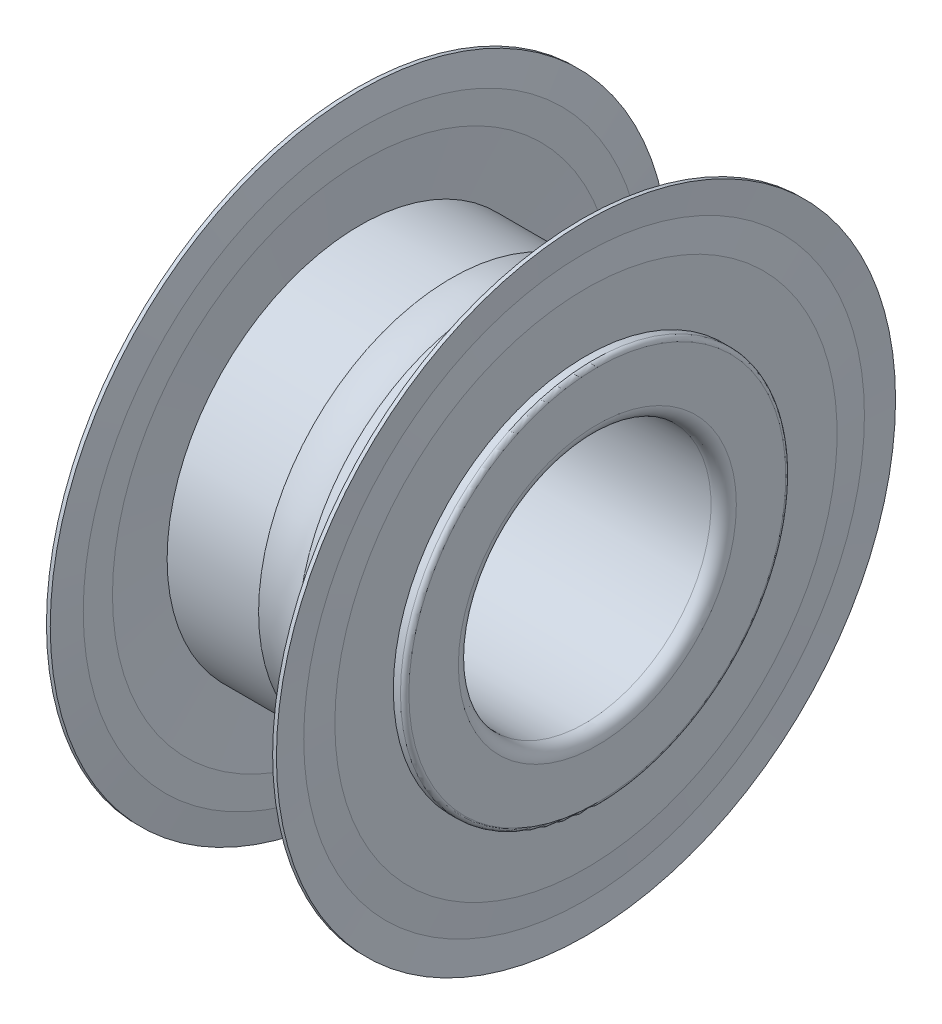
SolidWorks part; units mm, degrees
ref_plane "Front Plane" through (0, 0, 0) normal (0, 0, 1) x (1, 0, 0)
ref_plane "Top Plane" through (0, 0, 0) normal (0, 1, 0) x (1, 0, 0)
ref_plane "Right Plane" through (0, 0, 0) normal (1, 0, 0) x (0, 0, -1)
ref_plane "Plane1"
sketch "Sketch1" plane through (0, 0, 0) normal (0, 0, 1) x (1, 0, 0)
  line L0 (0, 2.9833) -> (0, 2.2)
  line L1 (0.2, 2) -> (3.8, 2)
  line L2 (4, 2.2) -> (4, 2.9833)
  line L3 (3.9333, 3.05) -> (2.3122, 3.05)
  line L4 (1.6878, 3.05) -> (0.0667, 3.05)
  line L5 (50, 0) -> (-50, 0) construction
  arc A0 (0, 2.2) -> (0.2, 2) centre (0.2, 2.2) ccw
  arc A1 (3.8, 2) -> (4, 2.2) centre (3.8, 2.2) ccw
  arc A2 (4, 2.9833) -> (3.9333, 3.05) centre (3.9333, 2.9833) ccw
  arc A3 (1.6878, 3.05) -> (2.3122, 3.05) centre (2, 4) ccw
  arc A4 (0.0667, 3.05) -> (0, 2.9833) centre (0.0667, 2.9833) ccw
revolve "Revolução1" add sketch "Sketch1" angle 360 about L5
ref_plane "Plane2"
sketch "Sketch2" plane through (0, 0, 0) normal (0, 0, 1) x (1, 0, 0)
  line L0 (0.18, 4.9) -> (0.21, 4.4375)
  line L1 (0.21, 4.4375) -> (0.18, 3.975)
  line L2 (0.18, 3.975) -> (0.18, 3.05)
  line L3 (0.18, 3.05) -> (0.24, 3.05)
  line L4 (0.24, 3.05) -> (0.3, 3.975)
  line L5 (0.3, 3.975) -> (0.3, 4.4375)
  line L6 (0.3, 4.4375) -> (0.24, 4.9)
  line L7 (0.24, 4.9) -> (0.18, 4.9)
  line L8 (50, 0) -> (-50, 0) construction
revolve "Revolução2" add sketch "Sketch2" angle 360 about L8
ref_plane "Plane3"
sketch "Sketch3" plane through (0, 0, 0) normal (0, 0, 1) x (1, 0, 0)
  line L0 (3.7, 4.4375) -> (3.7, 3.975)
  line L1 (3.7, 3.975) -> (3.76, 3.05)
  line L2 (3.76, 3.05) -> (3.82, 3.05)
  line L3 (3.82, 3.05) -> (3.82, 3.975)
  line L4 (3.82, 3.975) -> (3.79, 4.4375)
  line L5 (3.79, 4.4375) -> (3.82, 4.9)
  line L6 (3.82, 4.9) -> (3.76, 4.9)
  line L7 (3.76, 4.9) -> (3.7, 4.4375)
  line L8 (50, 0) -> (-50, 0) construction
revolve "Revolução3" add sketch "Sketch3" angle 360 about L8
